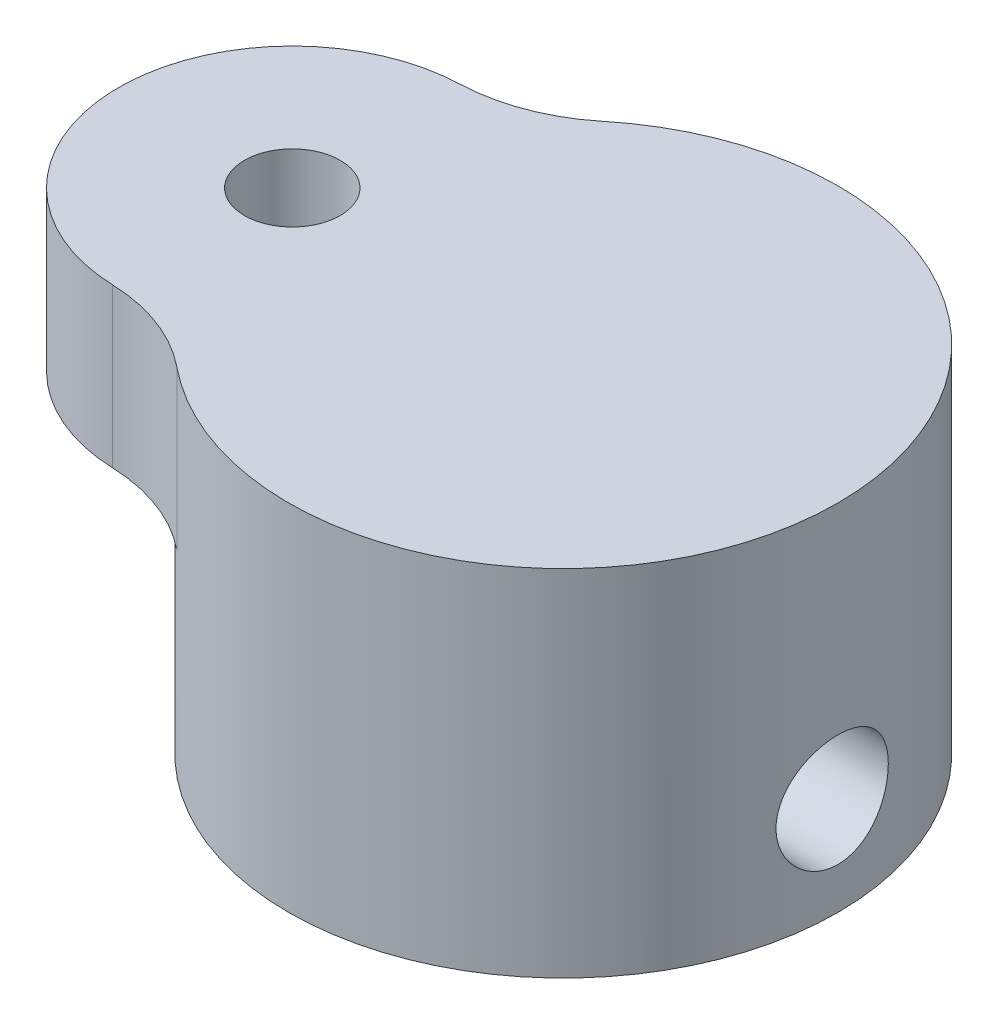
SolidWorks part; units mm, degrees
ref_plane "Front Plane" through (0, 0, 0) normal (0, 0, 1) x (1, 0, 0)
ref_plane "Top Plane" through (0, 0, 0) normal (0, 1, 0) x (1, 0, 0)
ref_plane "Right Plane" through (0, 0, 0) normal (1, 0, 0) x (0, 0, -1)
sketch "Sketch1" plane through (0, 0, 0) normal (0, 1, 0) x (1, 0, 0)
  circle A0 centre (0, 0) radius 10.033
  circle A1 centre (0, 0) radius 6.35
  dimension "D1" = 12.7
  dimension "D2" = 20.066
extrude "Boss-Extrude1" add sketch "Sketch1" along normal blind 7.1628
sketch "Sketch2" plane through (0, 0, 0) normal (1, 0, 0) x (0, 0, -1)
  line L0 (-10.033, 0) -> (10.033, 0) construction
  circle A0 centre (0, 3.5687) radius 2.0511
  point P4 (-0.4661, 3.5687)
  dimension "D2" = 4.1021
  dimension "D1" = 3.5687
extrude "Cut-Extrude1" cut sketch "Sketch2" against normal through all both and the other way through all
sketch "Sketch3" plane through (0, 7.1628, 0) normal (0, 1, 0) x (1, 0, 0)
  line L0 (0, -10.033) -> (0, 10.033) construction
  line L1 (0, 0) -> (-9.899, 0) construction
  circle A0 centre (0, 0) radius 10.033 construction
  circle A1 centre (-9.899, 0) radius 1.75
  arc A2 (-6.3444, -7.7724) -> (-6.3444, 7.7724) centre (0, 0) ccw
  arc A3 (-10.1294, 6.3458) -> (-10.1294, -6.3458) centre (-9.899, 0) ccw
  arc A4 (-6.3444, 7.7724) -> (-10.1294, 6.3458) centre (-10.3598, 12.6916) cw
  arc A5 (-6.3444, -7.7724) -> (-10.1294, -6.3458) centre (-10.3598, -12.6916) ccw
  point P13 (-8.5902, 4.9191)
  dimension "D1" = 3.5
  dimension "D3" = 6.35
  dimension "D4" = 6.35
  dimension "D2" = 9.899
extrude "Boss-Extrude2" add sketch "Sketch3" along normal blind 5.7912
